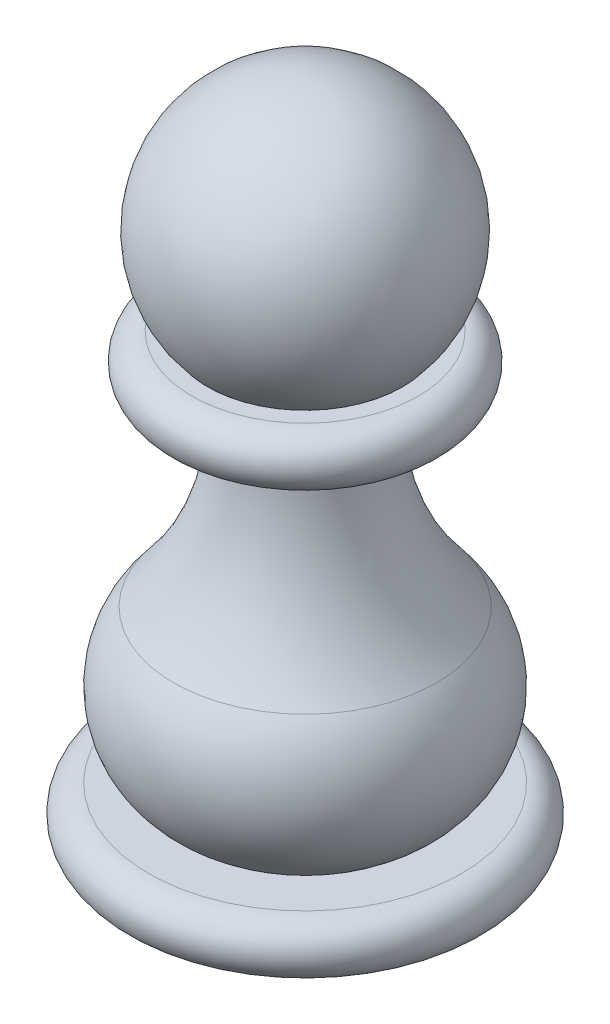
SolidWorks part; units mm, degrees
material "ABS"
ref_plane "Front Plane" through (0, 0, 0) normal (0, 0, 1) x (1, 0, 0)
ref_plane "Top Plane" through (0, 0, 0) normal (0, 1, 0) x (1, 0, 0)
ref_plane "Right Plane" through (0, 0, 0) normal (1, 0, 0) x (0, 0, -1)
sketch "Sketch1" plane through (0, 0, 0) normal (0, 0, 1) x (1, 0, 0)
  line L0 (0, 0) -> (0, 38) construction
  line L1 (0, 0) -> (9, 0)
  line L2 (9, 3) -> (6.5, 3)
  line L3 (0, 38) -> (0, 0)
  line L4 (4, 22.5) -> (6.5, 22.5)
  line L5 (6.5, 25.5) -> (5.5902, 25.5)
  arc A0 (9, 0) -> (9, 3) centre (9, 1.5) ccw
  arc A1 (6.5, 3) -> (7.5621, 11.7704) centre (3, 7.8734) ccw
  arc A2 (7.5621, 11.7704) -> (4, 22.5) centre (18.9675, 21.513) cw
  arc A3 (6.5, 22.5) -> (6.5, 25.5) centre (6.5, 24) ccw
  arc A4 (5.5902, 25.5) -> (0, 38) centre (0, 30.5) ccw
  dimension "D3" = 1.5
  dimension "D4" = 9
  dimension "D5" = 6
  dimension "D6" = 15
  dimension "D9" = 1.5
  dimension "D10" = 7.5
  dimension "D1" = 9
  dimension "D2" = 6.5
  dimension "D7" = 4
  dimension "D8" = 6.5
  dimension "D11" = 38
  dimension "D12" = 12.5
revolve "Revolve1" add sketch "Sketch1" angle 360 about L0
